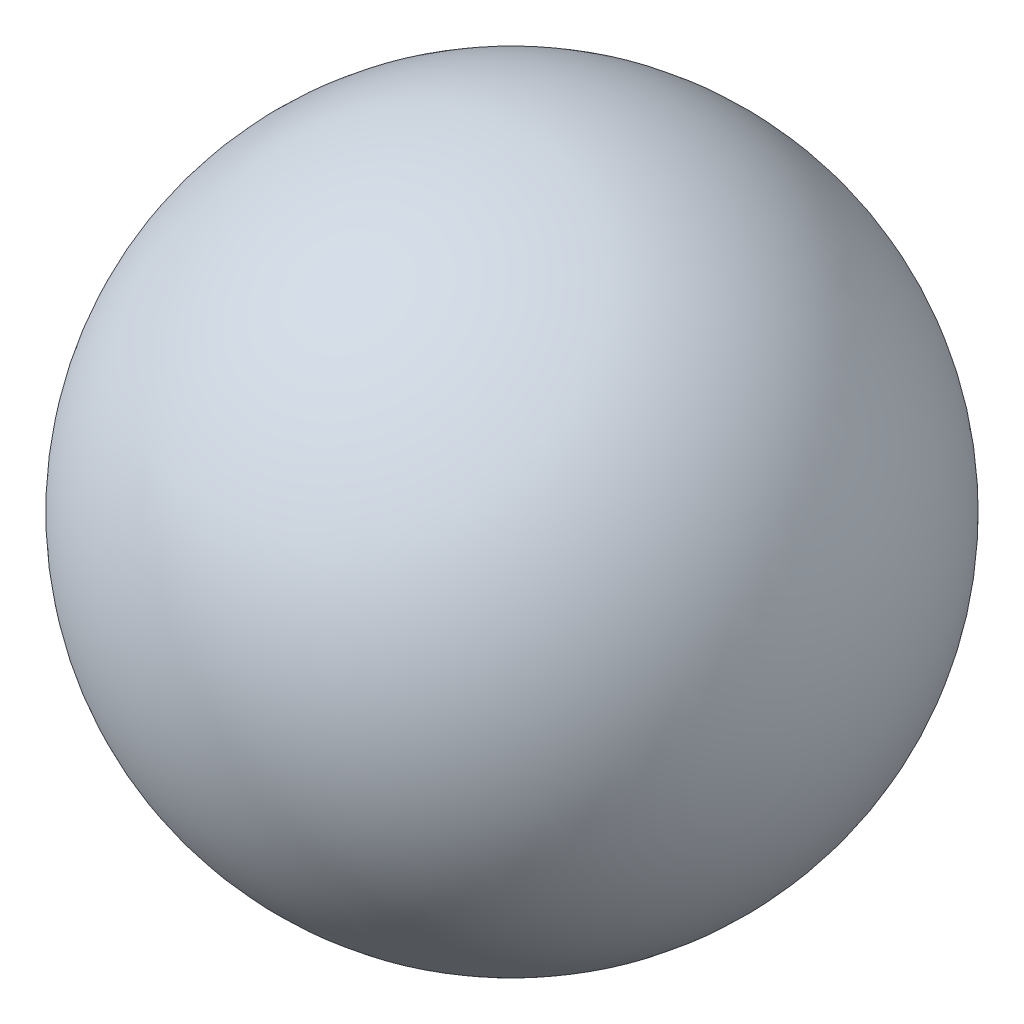
SolidWorks part; units mm, degrees
ref_plane "Front Plane" through (0, 0, 0) normal (0, 0, 1) x (1, 0, 0)
ref_plane "Top Plane" through (0, 0, 0) normal (0, 1, 0) x (1, 0, 0)
ref_plane "Right Plane" through (0, 0, 0) normal (1, 0, 0) x (0, 0, -1)
sketch "Sketch1" plane through (0, 0, 0) normal (0, 0, 1) x (1, 0, 0)
  line L0 (0, 0) -> (0, 82.55)
  arc A0 (0, 82.55) -> (0, 0) centre (0, 41.275) ccw
  dimension "D1" = 82.55
revolve "Revolve1" add sketch "Sketch1" angle 360 about L0
